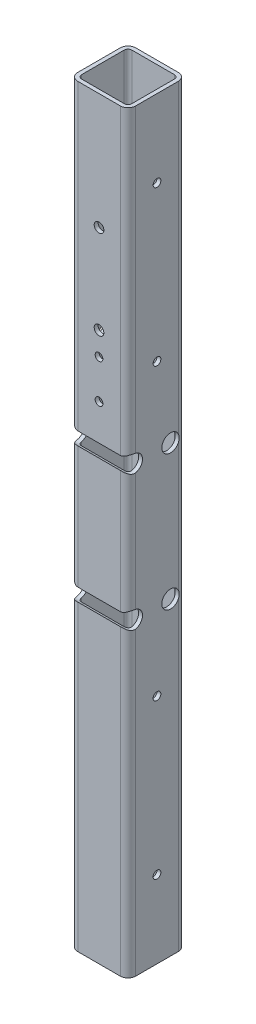
SolidWorks part; units mm, degrees
material "AISI 1010 钢，热轧条材"
ref_plane "前视基准面" through (0, 0, 0) normal (0, 0, 1) x (1, 0, 0)
ref_plane "上视基准面" through (0, 0, 0) normal (0, 1, 0) x (1, 0, 0)
ref_plane "右视基准面" through (0, 0, 0) normal (1, 0, 0) x (0, 0, -1)
sketch "草图1" plane through (0, 0, 0) normal (0, 1, 0) x (1, 0, 0)
  line L0 (4, 2) -> (26, 2)
  line L1 (4, 0) -> (26, 0)
  line L2 (0, 4) -> (0, 26)
  line L3 (4, 30) -> (26, 30)
  line L4 (30, 4) -> (30, 26)
  line L5 (28, 4) -> (28, 26)
  line L6 (4, 28) -> (26, 28)
  line L7 (2, 4) -> (2, 26)
  arc A0 (4, 0) -> (0, 4) centre (4, 4) cw
  arc A1 (26, 0) -> (30, 4) centre (26, 4) ccw
  arc A2 (26, 30) -> (30, 26) centre (26, 26) cw
  arc A3 (0, 26) -> (4, 30) centre (4, 26) cw
  arc A4 (26, 2) -> (28, 4) centre (26, 4) ccw
  arc A5 (26, 28) -> (28, 26) centre (26, 26) cw
  arc A6 (2, 26) -> (4, 28) centre (4, 26) cw
  arc A7 (4, 2) -> (2, 4) centre (4, 4) cw
  point P7 (0, 0)
  point P10 (30, 0)
  point P13 (30, 30)
  point P16 (0, 30)
  dimension "D3" = 4
  dimension "D1" = 30
  dimension "D2" = 30
  dimension "D4" = 2
extrude "凸台-拉伸1" add sketch "草图1" along normal mid plane 390
sketch "草图2" plane through (0, 0, 0) normal (1, 0, 0) x (0, 0, -1)
  line L0 (4, -195) -> (26, -195) construction
  line L1 (0, 0) -> (30, 0) construction
  line L2 (30, 195) -> (30, -195) construction
  circle A0 centre (3, -35) radius 4.5
  circle A1 centre (22, -35) radius 4.5
  circle A2 centre (22, 35) radius 4.5
  circle A3 centre (3, 35) radius 4.5
  circle A4 centre (15, -155) radius 2
  circle A5 centre (15, -75) radius 2
  circle A6 centre (15, 75) radius 2
  circle A7 centre (15, 155) radius 2
  dimension "D1" = 9
  dimension "D7" = 4
  dimension "D2" = 8
  dimension "D3" = 27
  dimension "D4" = 70
  dimension "D5" = 40
  dimension "D6" = 80
  dimension "D8" = 15
extrude "切除-拉伸1" cut sketch "草图2" along normal through all
sketch "草图3" plane through (0, 0, 0) normal (0, 0, 1) x (1, 0, 0)
  line L0 (4, -195) -> (26, -195) construction
  line L1 (4, 195) -> (26, 195) construction
  circle A0 centre (15, 89) radius 2.5
  circle A1 centre (15, 135) radius 2.5
  circle A2 centre (15, 77) radius 2
  circle A3 centre (15, 57) radius 2
  point P7 (15, -195)
  dimension "D1" = 5
  dimension "D4" = 4
  dimension "D2" = 46
  dimension "D3" = 60
  dimension "D5" = 20
  dimension "D6" = 12
extrude "切除-拉伸2" cut sketch "草图3" against normal through all
